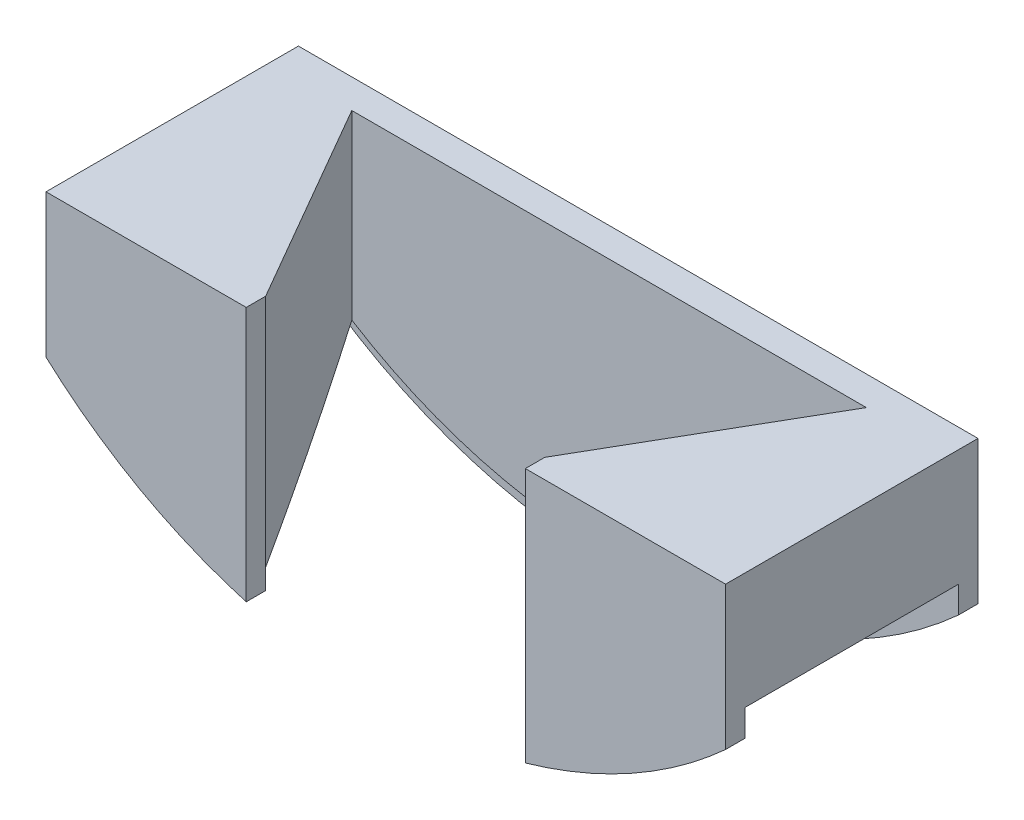
SolidWorks part; units mm, degrees
ref_plane "Front" through (0, 0, 0) normal (0, 0, 1) x (1, 0, 0)
ref_plane "Top" through (0, 0, 0) normal (0, 1, 0) x (1, 0, 0)
ref_plane "Right" through (0, 0, 0) normal (1, 0, 0) x (0, 0, -1)
sketch "Sketch1" plane through (0, 0, 0) normal (0, 0, 1) x (1, 0, 0)
  line L1 (-17.5, -3) -> (17.5, -3)
  line L2 (-17.5, -3) -> (-17.5, 3)
  line L3 (-17.5, 3) -> (17.5, 3)
  line L4 (17.5, -3) -> (17.5, 3)
  line L5 (-17.5, -3) -> (17.5, 3) construction
  line L6 (-17.5, 3) -> (17.5, -3) construction
  point P0 (0, 0)
  dimension "D1" = 35
  dimension "D2" = 6
extrude "Boss-Extrude1" add sketch "Sketch1" along normal blind 12
sketch "Sketch2" plane through (0, 0, 12) normal (0, 0, 1) x (1, 0, 0)
  line L0 (-17.5, -3) -> (17.5, -3) construction
  line L1 (-17.5, -3) -> (17.5, -3)
  arc A0 (-17.5, -3) -> (17.5, -3) centre (0, 14.8536) ccw
  dimension "D1" = 50
extrude "Boss-Extrude2" add sketch "Sketch2" against normal blind 12
sketch "Sketch4" plane through (0, 0, 12) normal (0, 0, 1) x (1, 0, 0)
  line L0 (17.5, 3) -> (-17.5, 3) construction
  line L1 (-3, 3) -> (3, 3)
  line L2 (-3, 3) -> (-3, -10.1464)
  line L3 (-3, -10.1464) -> (3, -10.1464)
  line L4 (3, 3) -> (3, -10.1464)
  arc A0 (-17.5, -3) -> (17.5, -3) centre (0, 14.8536) ccw construction
  point P10 (0, 3)
  dimension "D1" = 6
extrude "Cut-Extrude1" cut sketch "Sketch4" against normal blind 8
sketch "Sketch5" plane through (0, 0, 12) normal (0, 0, 1) x (1, 0, 0)
  line L0 (3, 2) -> (3.75, 2) construction
  line L1 (3, 4) -> (3.75, 4) construction
  line L2 (3, -9.9658) -> (3, 3) construction
  line L3 (3.75, 2.7402) -> (3, 2.7402) construction
  line L4 (3.75, 2.7402) -> (3.75, 2) construction
  line L5 (3.75, 3.2598) -> (3.75, 4) construction
  line L6 (3, 2) -> (3, 4)
  line L7 (17.5, 3) -> (3, 3) construction
  line L8 (3, -9.9658) -> (3, 3) construction
  line L9 (3.75, 3.2598) -> (3.75, 2.7402)
  arc A0 (3.3118, 2.4989) -> (3, 2) centre (3.555, 2) ccw
  arc A1 (3.6196, 2.5915) -> (3.3118, 2.4989) centre (3.75, 1.6) ccw
  arc A2 (3.6196, 2.5915) -> (3.75, 2.7402) centre (3.6, 2.7402) ccw
  arc A3 (3.3118, 3.5011) -> (3, 4) centre (3.555, 4) cw
  arc A4 (3.6196, 3.4085) -> (3.3118, 3.5011) centre (3.75, 4.4) cw
  arc A5 (3.6196, 3.4085) -> (3.75, 3.2598) centre (3.6, 3.2598) cw
  point P6 (3, 2)
  dimension "D4" = 1.11
  dimension "D7" = 0.3
  dimension "D8" = 1
  dimension "D1" = 0.6196
  dimension "D2" = 0.75
  dimension "D3" = 1
  dimension "D6" = 0.4
extrude "Cut-Extrude2" cut sketch "Sketch5" against normal blind 8
pattern_linear "LPattern2" count 10 spacing 2 along (0, -1, 0) of "Cut-Extrude2"
mirror "Mirror1" about plane through (0, 0, 0) normal (1, 0, 0) of "LPattern2", "Cut-Extrude2"
sketch "Sketch6" plane through (0, 3, 0) normal (0, 1, 0) x (1, 0, 0)
  line L0 (7.1878, -12) -> (-7.1878, -12)
  line L1 (17.5, -12) -> (3.75, -12) construction
  line L3 (-7.1878, -12) -> (-13.25, -1.5)
  line L4 (-13.25, -1.5) -> (13.25, -1.5)
  line L5 (13.25, -1.5) -> (7.1878, -12)
  line L6 (-3.75, -12) -> (-17.5, -12) construction
  point P6 (0, -12)
  point P9 (0, -1.5)
  dimension "D1" = 60
  dimension "D2" = 26.5
  dimension "D3" = 10.5
extrude "Cut-Extrude3" cut sketch "Sketch6" against normal through all
sketch "Sketch7" plane through (0, 0, 12) normal (0, 0, 1) x (1, 0, 0)
  line L3 (17.5, 3) -> (7.1878, 3)
  line L4 (7.1878, 3) -> (7.1878, -9.0908)
  line L5 (17.5, -3) -> (17.5, 3)
  line L6 (17.5, 3) -> (7.1878, 3)
  line L7 (7.1878, 3) -> (7.1878, -10.1331)
  line L8 (17.5, -4.3753) -> (17.5, 3)
  arc A0 (7.1878, -10.1331) -> (17.5, -4.3753) centre (0, 14.8536) ccw
  arc A1 (7.1878, -9.0908) -> (17.5, -3) centre (0, 14.8536) ccw
  arc A2 (7.1878, -9.0908) -> (17.5, -3) centre (0, 14.8536) ccw construction
  dimension "D2" = 1
  dimension "D3" = 7.3753
  dimension "D4" = 13.1331
  dimension "D1" = 0
extrude "Boss-Extrude3" add sketch "Sketch7" along normal blind 1 contours A0 L8 L6 L7
mirror "Mirror2" about plane through (0, 0, 0) normal (1, 0, 0) of "Boss-Extrude3"
sketch "Sketch8" plane through (0, 0, 0) normal (0, 0, -1) x (-1, 0, 0)
  line L0 (17.5, -4.3753) -> (17.5, -3) construction
  line L1 (-17.5, -4.3753) -> (-17.5, -3) construction
  line L2 (17.5, -4.3753) -> (17.5, -3)
  line L3 (-17.5, -4.3753) -> (-17.5, -3)
  arc A1 (-17.5, -3) -> (17.5, -3) centre (0, 14.8536) ccw construction
  arc A2 (-18.2, -3.7141) -> (18.2, -3.7141) centre (0, 14.8536) ccw
  arc A3 (-17.5, -4.3753) -> (17.5, -4.3753) centre (0, 14.8536) ccw
  arc A4 (-17.5, -3) -> (17.5, -3) centre (0, 14.8536) ccw
  dimension "D1" = 1
extrude "Boss-Extrude4" add sketch "Sketch8" against normal blind 1
